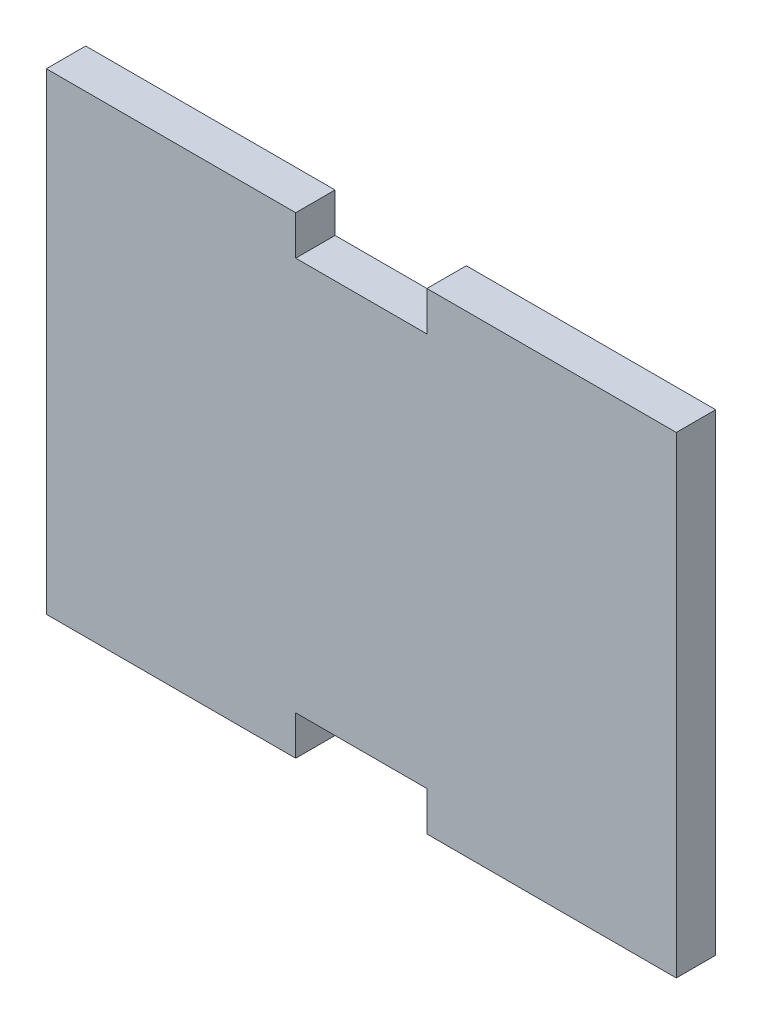
SolidWorks part; units mm, degrees
ref_plane "Front Plane" through (0, 0, 0) normal (0, 0, 1) x (1, 0, 0)
ref_plane "Top Plane" through (0, 0, 0) normal (0, 1, 0) x (1, 0, 0)
ref_plane "Right Plane" through (0, 0, 0) normal (1, 0, 0) x (0, 0, -1)
sketch "Sketch1" plane through (0, 0, 0) normal (0, 0, 1) x (1, 0, 0)
  line L0 (-23.6279, 43.1512) -> (-23.6279, 40.1512)
  line L1 (-42.6279, 43.1512) -> (-23.6279, 43.1512)
  line L2 (-42.6279, 43.1512) -> (-42.6279, 7.1512)
  line L3 (-42.6279, 7.1512) -> (-23.6279, 7.1512)
  line L4 (5.3721, 43.1512) -> (5.3721, 7.1512)
  line L5 (-42.6279, 43.1512) -> (5.3721, 7.1512) construction
  line L6 (-42.6279, 7.1512) -> (5.3721, 43.1512) construction
  line L7 (-23.6279, 40.1512) -> (-13.6279, 40.1512)
  line L8 (-13.6279, 40.1512) -> (-13.6279, 43.1512)
  line L9 (-23.6279, 7.1512) -> (-23.6279, 10.1512)
  line L10 (-23.6279, 10.1512) -> (-13.6279, 10.1512)
  line L11 (-13.6279, 10.1512) -> (-13.6279, 7.1512)
  line L12 (-13.6279, 43.1512) -> (5.3721, 43.1512)
  line L13 (-13.6279, 7.1512) -> (5.3721, 7.1512)
  point P0 (-18.6279, 25.1512)
  dimension "D1" = 36
  dimension "D2" = 48
  dimension "D3" = 10
  dimension "D4" = 3
  dimension "D5" = 19
  dimension "D6" = 10
  dimension "D7" = 3
extrude "Boss-Extrude1" add sketch "Sketch1" along normal blind 3
